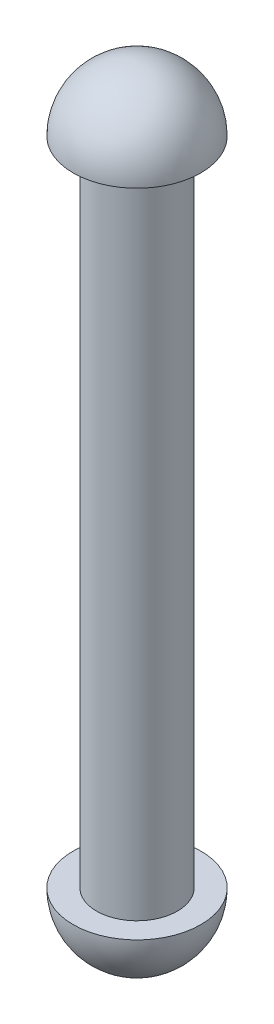
SolidWorks part; units mm, degrees
ref_plane "Front Plane" through (0, 0, 0) normal (0, 0, 1) x (1, 0, 0)
ref_plane "Top Plane" through (0, 0, 0) normal (0, 1, 0) x (1, 0, 0)
ref_plane "Right Plane" through (0, 0, 0) normal (1, 0, 0) x (0, 0, -1)
sketch "Sketch1" plane through (0, 0, 0) normal (0, 0, 1) x (1, 0, 0)
  line L0 (-30, 0) -> (-19, 0)
  line L1 (-19, 0) -> (-19, -306)
  line L2 (0, 30) -> (0, -336)
  line L4 (-30, -306) -> (-19, -306)
  arc A0 (0, 30) -> (-30, 0) centre (0, 0) ccw
  arc A1 (0, -336) -> (-30, -306) centre (0, -306) cw
  dimension "D1" = 60
  dimension "D3" = 19
revolve "Revolve4" add sketch "Sketch1" angle 360 about L2
